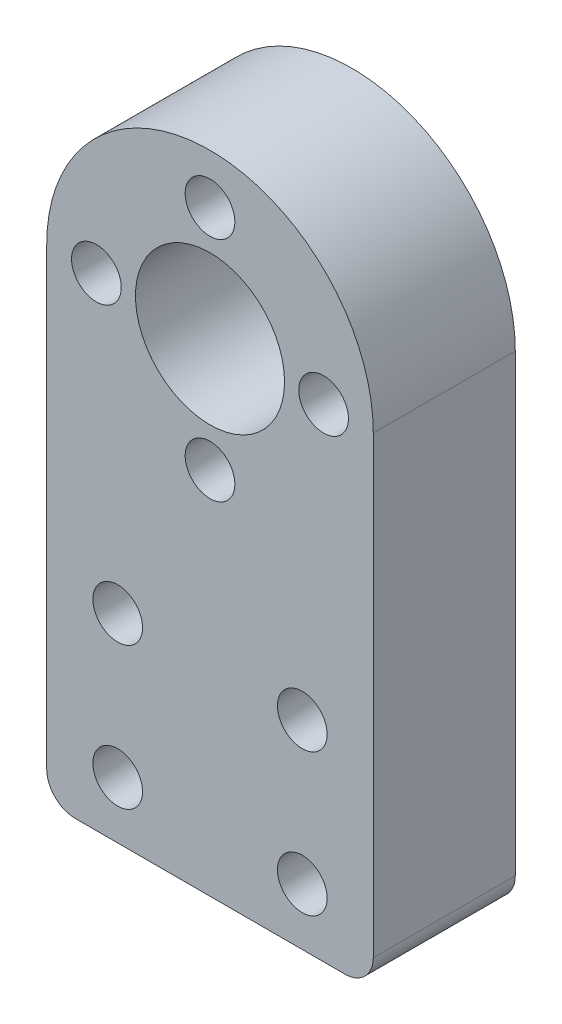
SolidWorks part; units mm, degrees
ref_plane "Front Plane" through (0, 0, 0) normal (0, 0, 1) x (1, 0, 0)
ref_plane "Top Plane" through (0, 0, 0) normal (0, 1, 0) x (1, 0, 0)
ref_plane "Right Plane" through (0, 0, 0) normal (1, 0, 0) x (0, 0, -1)
sketch "Sketch2" plane through (0, 0, 0) normal (0, 0, 1) x (1, 0, 0)
  line L6 (11.5, -17) -> (-11.5, -17)
  line L8 (11.5, -17) -> (11.5, 17)
  line L9 (11.5, 17) -> (-11.5, 17) construction
  line L10 (-11.5, -17) -> (-11.5, 17)
  line L11 (11.5, -17) -> (-11.5, 17) construction
  line L12 (11.5, 17) -> (-11.5, -17) construction
  arc A1 (11.5, 17) -> (-11.5, 17) centre (0, 17) ccw
  point P0 (0, 0)
  dimension "D1" = 23
  dimension "D2" = 34
extrude "Boss-Extrude1" add sketch "Sketch2" along normal blind 10
sketch "Sketch4" plane through (0, 0, 10) normal (0, 0, 1) x (1, 0, 0)
  circle A0 centre (0, 17) radius 5.25
  dimension "D1" = 10.5
extrude "Cut-Extrude1" cut sketch "Sketch4" against normal up to next
sketch "Sketch6" plane through (0, 0, 0) normal (0, 0, -1) x (-1, 0, 0)
  line L0 (-8, 17) -> (8, 17) construction
  line L1 (-11.5, 17) -> (11.5, 17) construction
  line L2 (0, 9) -> (0, 25) construction
  circle A0 centre (0, 25) radius 1.75
  circle A1 centre (8, 17) radius 1.75
  circle A2 centre (0, 9) radius 1.75
  circle A3 centre (-8, 17) radius 1.75
  point P6 (0, 17)
  point P11 (0, 17)
  dimension "D2" = 3.5
  dimension "D1" = 16
extrude "Cut-Extrude2" cut sketch "Sketch6" against normal up to next
sketch "Sketch7" plane through (0, 0, 0) normal (0, 0, -1) x (-1, 0, 0)
  line L0 (-6.5, -3) -> (6.5, -3) construction
  line L1 (11.5, -17) -> (-11.5, -17) construction
  line L2 (-6.5, -13) -> (6.5, -13) construction
  line L3 (-11.5, 1) -> (11.5, 1) construction
  line L4 (-11.5, -17) -> (-11.5, 17) construction
  line L5 (11.5, 17) -> (11.5, -17) construction
  line L6 (0, 5.5) -> (0, -5.5) construction
  circle A0 centre (-6.5, -3) radius 1.75
  circle A1 centre (6.5, -3) radius 1.75
  circle A2 centre (6.5, -13) radius 1.75
  circle A3 centre (-6.5, -13) radius 1.75
  point P3 (0, -3)
  point P10 (0, -13)
  dimension "D2" = 3.5
  dimension "D5" = 5
  dimension "D1" = 10
  dimension "D3" = 4
  dimension "D4" = 18
extrude "Cut-Extrude3" cut sketch "Sketch7" against normal up to next
fillet "Fillet1" radius 2 2 edges at (-11.5, -17, 5) (11.5, -17, 5)
